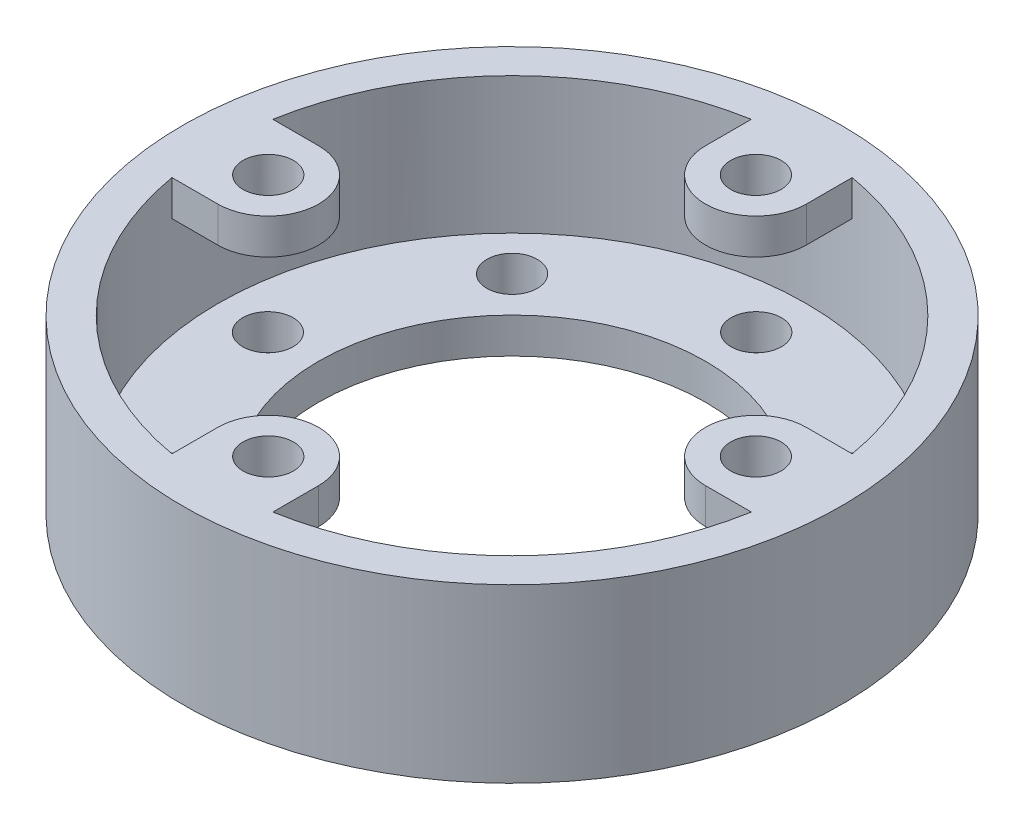
SolidWorks part; units mm, degrees
ref_plane "Front Plane" through (0, 0, 0) normal (0, 0, 1) x (1, 0, 0)
ref_plane "Top Plane" through (0, 0, 0) normal (0, 1, 0) x (1, 0, 0)
ref_plane "Right Plane" through (0, 0, 0) normal (1, 0, 0) x (0, 0, -1)
sketch "Sketch1" plane through (0, 0, 0) normal (0, 0, 1) x (1, 0, 0)
  line L0 (1690, 0) -> (2875, 0)
  line L1 (2875, 0) -> (2875, 1500)
  line L2 (2875, 1500) -> (2565, 1500)
  line L6 (2565, 310) -> (1690, 310)
  line L7 (1690, 310) -> (1690, 0)
  line L8 (2565, 310) -> (2565, 1500)
  line L9 (0, 0) -> (0, 587.9849) construction
  dimension "D1" = 1185
  dimension "D2" = 1690
  dimension "D3" = 1500
  dimension "D4" = 310
revolve "Revolve1" add sketch "Sketch1" angle 360 about L9
sketch "Sketch2" plane through (0, 310, 0) normal (0, 1, 0) x (1, 0, 0)
  circle A0 centre (2130, 0) radius 220
  point P2 (0, 0)
  dimension "D1" = 440
  dimension "D2" = 2130
extrude "Cut-Extrude1" cut sketch "Sketch2" against normal through all contours A0
pattern_circular "CirPattern1" count 8 over 360 about axis through (0, 0, 0) along (0, 1, 0) of "Cut-Extrude1"
sketch "Sketch8" plane through (0, 1500, 0) normal (0, 1, 0) x (1, 0, 0)
  line L2 (-440, 2526.9794) -> (-440, 2126.9794)
  line L4 (440, 2526.9794) -> (440, 2126.9794)
  circle A0 centre (0, 0) radius 2565 construction
  arc A1 (-440, 2126.9794) -> (440, 2126.9794) centre (0, 2126.9794) ccw
  circle A2 centre (0, 0) radius 2565 construction
  arc A3 (-440, 2526.9794) -> (440, 2526.9794) centre (0, 0) cw
  dimension "D1" = 400
  dimension "D2" = 880
extrude "Boss-Extrude1" add sketch "Sketch8" against normal blind 310 contours L2 A1 L4 A3
sketch "Sketch9" plane through (0, 1500, 0) normal (0, 1, 0) x (1, 0, 0)
  circle A0 centre (0, 2126.9794) radius 220
  point P2 (0, 0)
  point P4 (-142.5877, 2126.9794)
  point P5 (0, 0)
  dimension "D1" = 440
  dimension "D2" = 400
  dimension "D3" = 440
extrude "Cut-Extrude2" cut sketch "Sketch9" against normal up to next contours A0
pattern_circular "CirPattern2" count 4 over 360 about axis through (0, 0, 0) along (0, 1, 0) of "Boss-Extrude1", "Cut-Extrude2"
